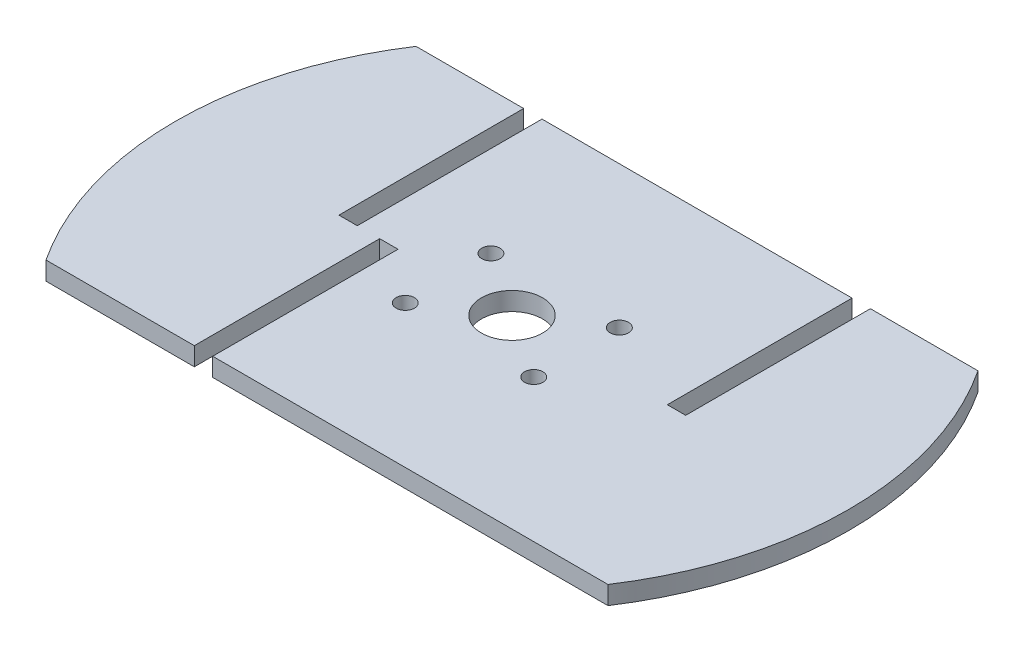
SolidWorks part; units mm, degrees
ref_plane "Front Plane" through (0, 0, 0) normal (0, 0, 1) x (1, 0, 0)
ref_plane "Top Plane" through (0, 0, 0) normal (0, 1, 0) x (1, 0, 0)
ref_plane "Right Plane" through (0, 0, 0) normal (1, 0, 0) x (0, 0, -1)
sketch "Sketch3" plane through (0, 0, 0) normal (0, 1, 0) x (1, 0, 0)
  line L0 (-42.1124, 3.703) -> (-22.1124, 3.703)
  line L1 (-22.1124, 3.703) -> (-22.1124, -26.497)
  line L2 (-22.1124, -26.497) -> (-19.1124, -26.497)
  line L3 (-19.1124, -26.497) -> (-19.1124, 3.703)
  line L4 (-19.1124, 3.703) -> (-15.4524, 3.703)
  line L8 (-12.4524, 3.703) -> (31.5776, 3.703)
  line L9 (31.5776, 3.703) -> (31.5776, -26.497)
  line L10 (31.5776, -26.497) -> (34.5776, -26.497)
  line L11 (34.5776, -26.497) -> (34.5776, 3.703)
  line L12 (34.5776, 3.703) -> (54.5776, 3.703)
  line L13 (64.5776, -6.297) -> (64.5776, -46.797)
  line L14 (54.5776, -56.797) -> (-42.1124, -56.797)
  line L15 (-52.1124, -6.297) -> (-52.1124, -46.797)
  line L16 (-15.4524, 3.703) -> (-12.4524, 3.703)
  arc A0 (54.5776, 3.703) -> (64.5776, -6.297) centre (54.5776, -6.297) cw
  arc A1 (-52.1124, -6.297) -> (-42.1124, 3.703) centre (-42.1124, -6.297) cw
  arc A2 (-42.1124, -56.797) -> (-52.1124, -46.797) centre (-42.1124, -46.797) cw
  arc A3 (54.5776, -56.797) -> (64.5776, -46.797) centre (54.5776, -46.797) ccw
  dimension "D8" = 10
  dimension "D1" = 60.5
  dimension "D2" = 3
  dimension "D4" = 3
  dimension "D5" = 30.2
  dimension "D6" = 44.03
  dimension "D7" = 3.66
  dimension "D9" = 30
  dimension "D10" = 30
extrude "Boss-Extrude1" add sketch "Sketch3" along normal blind 3 contours A3 L13 A0 L12 L11 L10 L9 L8 L16 L4 L3 L2 L1 L0 A1 L15 A2 L14
sketch "Sketch4" plane through (0, 3, 0) normal (0, 1, 0) x (1, 0, 0)
  line L0 (-52.1124, -6.297) -> (-52.1124, -46.797) construction
  line L2 (-19.1124, 3.703) -> (31.5776, 3.703) construction
  circle A0 centre (6.2326, -26.547) radius 5
  point P2 (0, 0)
  point P3 (0, 0)
  point P4 (8.7547, -30.5041)
  point P7 (-52.1124, -26.547)
  point P8 (0, 0)
  point P9 (-52.1124, -26.547)
  point P10 (0, 0)
  point P13 (0, 0)
  point P15 (0, 0)
  point P16 (0, -24.8511)
  point P17 (9.9897, -32.6209)
  point P18 (0, 0)
  point P21 (6.2326, 3.703)
extrude "Cut-Extrude1" cut sketch "Sketch4" against normal blind 3 contours A0
sketch "Sketch6" plane through (0, 3, 0) normal (0, 1, 0) x (1, 0, 0)
  circle A0 centre (-4.2674, -19.497) radius 1.5
  circle A1 centre (-4.2674, -33.497) radius 1.5
  circle A2 centre (16.7326, -19.497) radius 1.5
  circle A3 centre (16.7326, -33.497) radius 1.5
  circle A4 centre (6.2326, -26.547) radius 5 construction
  dimension "D2" = 7
  dimension "D1" = 7
  dimension "D3" = 10.5
  dimension "D4" = 10.5
  dimension "D5" = 10.5
  dimension "D6" = 10.5
  dimension "D7" = 7
  dimension "D8" = 7
extrude "Cut-Extrude2" cut sketch "Sketch6" against normal blind 3
sketch "Sketch7" plane through (0, 3, 0) normal (0, 1, 0) x (1, 0, 0)
  line L0 (-42.1124, 3.703) -> (-22.1124, 3.703) construction
  line L1 (54.5776, -56.797) -> (-42.1124, -56.797) construction
  line L2 (34.5776, 3.703) -> (54.5776, 3.703) construction
  line L3 (52.1667, 3.703) -> (73.4592, 3.703)
  line L4 (73.4592, 3.703) -> (73.4592, -56.797)
  line L5 (73.4592, -56.797) -> (52.1667, -56.797)
  line L6 (-39.7014, 3.703) -> (-60.8199, 3.703)
  line L7 (-60.8199, 3.703) -> (-60.8199, -56.797)
  line L8 (-60.8199, -56.797) -> (-39.7014, -56.797)
  arc A0 (-39.7014, -56.797) -> (-39.7014, 3.703) centre (6.2326, -26.547) cw
  circle A1 centre (6.2326, -26.547) radius 5 construction
  arc A2 (52.1667, 3.703) -> (52.1667, -56.797) centre (6.2326, -26.547) cw
extrude "Cut-Extrude3" cut sketch "Sketch7" against normal blind 3
sketch "Sketch8" plane through (0, 3, 0) normal (0, 1, 0) x (1, 0, 0)
  line L0 (-15.4524, -56.797) -> (-15.4524, -26.497)
  line L1 (52.1667, -56.797) -> (-39.7014, -56.797) construction
  line L2 (-15.4524, -26.497) -> (-12.4524, -26.497)
  line L3 (-12.4524, -26.497) -> (-12.4524, -56.797)
  line L4 (-12.4524, -56.797) -> (-15.4524, -56.797)
  dimension "D1" = 3.66
  dimension "D2" = 3
extrude "Cut-Extrude4" cut sketch "Sketch8" against normal blind 3
